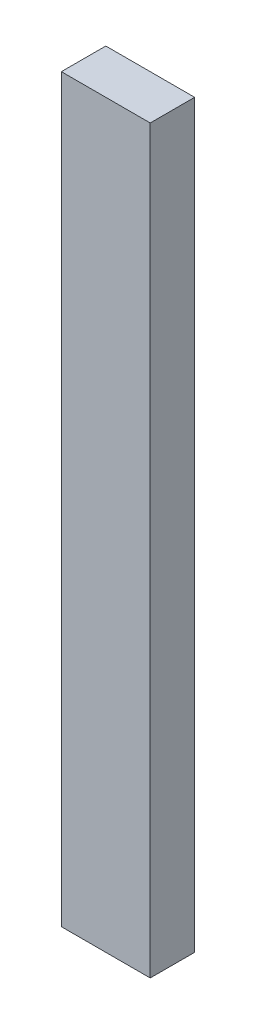
SolidWorks part; units mm, degrees
ref_plane "Front Plane" through (0, 0, 0) normal (0, 0, 1) x (1, 0, 0)
ref_plane "Top Plane" through (0, 0, 0) normal (0, 1, 0) x (1, 0, 0)
ref_plane "Right Plane" through (0, 0, 0) normal (1, 0, 0) x (0, 0, -1)
sketch "Sketch1" plane through (0, 0, 0) normal (0, 0, 1) x (1, 0, 0)
  line L1 (-6, -50) -> (6, -50) construction
  line L2 (-6, -50) -> (-6, 50) construction
  line L3 (-6, 50) -> (6, 50) construction
  line L4 (6, -50) -> (6, 50) construction
  line L5 (-6, -50) -> (6, -50)
  line L6 (-6, -50) -> (-6, 50)
  line L7 (-6, 50) -> (6, 50)
  line L8 (6, -50) -> (6, 50)
  line L9 (-6, -50) -> (6, 50) construction
  line L10 (-6, 50) -> (6, -50) construction
  point P0 (0, 0)
  point P6 (0, 0)
  dimension "D1" = 100
  dimension "D2" = 12
extrude "Boss-Extrude1" add sketch "Sketch1" along normal blind 6
